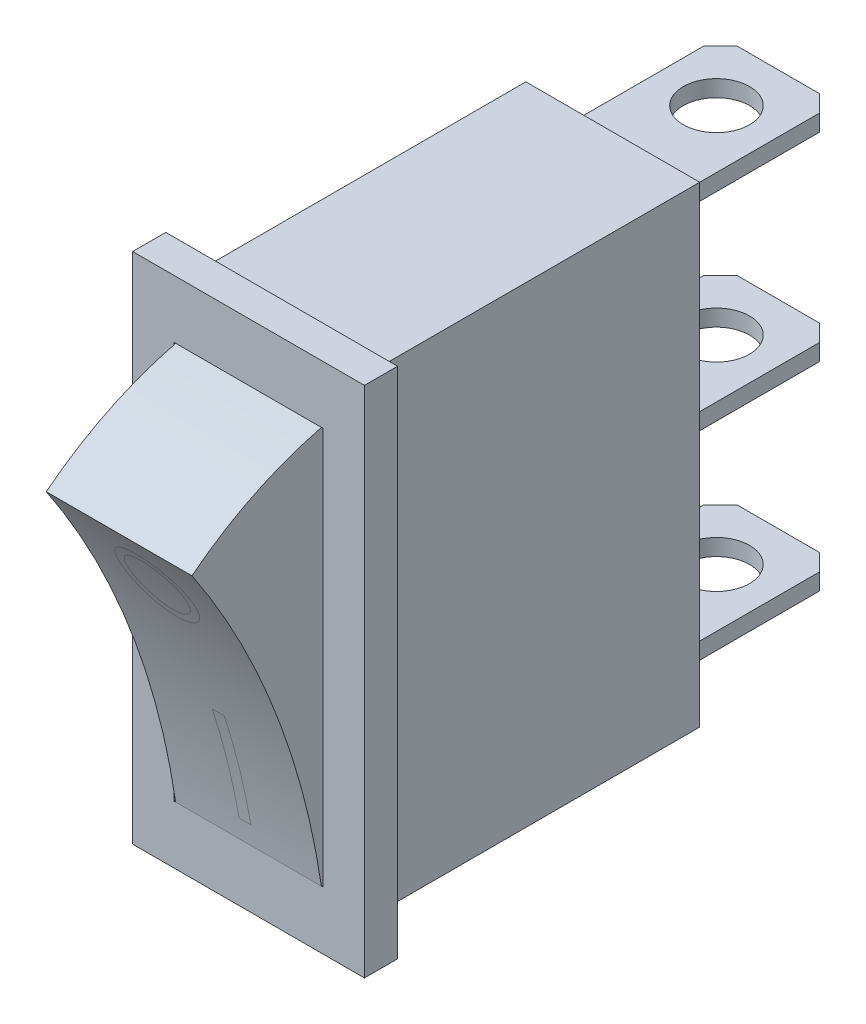
SolidWorks part; units mm, degrees
material "ABS"
ref_plane "Front Plane" through (0, 0, 0) normal (0, 0, 1) x (1, 0, 0)
ref_plane "Top Plane" through (0, 0, 0) normal (0, 1, 0) x (1, 0, 0)
ref_plane "Right Plane" through (0, 0, 0) normal (1, 0, 0) x (0, 0, -1)
sketch "Sketch1" plane through (0, 0, 0) normal (0, 0, 1) x (1, 0, 0)
  line L1 (-7, 15.5) -> (7, 15.5)
  line L2 (-7, 15.5) -> (-7, -15.5)
  line L3 (-7, -15.5) -> (7, -15.5)
  line L4 (7, 15.5) -> (7, -15.5)
  line L5 (-7, 15.5) -> (7, -15.5) construction
  line L6 (-7, -15.5) -> (7, 15.5) construction
  line L7 (-4.5, 12) -> (4.5, 12)
  line L8 (-4.5, 12) -> (-4.5, -12)
  line L9 (-4.5, -12) -> (4.5, -12)
  line L10 (4.5, 12) -> (4.5, -12)
  line L11 (-4.5, 12) -> (4.5, -12) construction
  line L12 (-4.5, -12) -> (4.5, 12) construction
  point P0 (0, 0)
  point P6 (0, 0)
  dimension "D1" = 31
  dimension "D2" = 14
  dimension "D3" = 24
  dimension "D4" = 9
extrude "Boss-Extrude1" add sketch "Sketch1" along normal blind 2
sketch "Sketch2" plane through (0, 0, 0) normal (0, 0, 1) x (1, 0, 0)
  line L0 (4.5, -12) -> (4.5, 12) construction
  line L1 (-5.25, 14.25) -> (5.25, 14.25)
  line L2 (-5.25, 14.25) -> (-5.25, -14.25)
  line L3 (-5.25, -14.25) -> (5.25, -14.25)
  line L4 (5.25, 14.25) -> (5.25, -14.25)
  line L5 (-5.25, 14.25) -> (5.25, -14.25) construction
  line L6 (-5.25, -14.25) -> (5.25, 14.25) construction
  line L7 (-4.5, -12) -> (4.5, -12) construction
  line L8 (-4.5, 12) -> (-4.5, -12) construction
  line L9 (4.5, 12) -> (-4.5, 12) construction
  line L10 (4.5, -12) -> (4.5, 12)
  line L11 (-4.5, -12) -> (4.5, -12)
  line L12 (-4.5, 12) -> (-4.5, -12)
  line L13 (4.5, 12) -> (-4.5, 12)
  point P0 (0, 0)
  dimension "D1" = 10.5
  dimension "D2" = 28.5
extrude "Boss-Extrude2" add sketch "Sketch2" against normal blind 20
sketch "Sketch3" plane through (0, 0, -20) normal (0, 0, -1) x (-1, 0, 0)
  line L4 (-5.25, 14.25) -> (-5.25, -14.25)
  line L5 (-5.25, -14.25) -> (5.25, -14.25)
  line L6 (5.25, -14.25) -> (5.25, 14.25)
  line L7 (5.25, 14.25) -> (-5.25, 14.25)
  line L8 (-5.25, 14.25) -> (-5.25, -14.25)
  line L9 (-5.25, -14.25) -> (5.25, -14.25)
  line L10 (5.25, -14.25) -> (5.25, 14.25)
  line L11 (5.25, 14.25) -> (-5.25, 14.25)
  dimension "D1" = 0
extrude "Boss-Extrude3" add sketch "Sketch3" against normal blind 2
sketch "Sketch4" plane through (0, 0, -20) normal (0, 0, -1) x (-1, 0, 0)
  line L1 (-3.5, 0.5) -> (3.5, 0.5)
  line L2 (-3.5, 0.5) -> (-3.5, -0.5)
  line L3 (-3.5, -0.5) -> (3.5, -0.5)
  line L4 (3.5, 0.5) -> (3.5, -0.5)
  line L5 (-3.5, 0.5) -> (3.5, -0.5) construction
  line L6 (-3.5, -0.5) -> (3.5, 0.5) construction
  point P0 (0, 0)
  dimension "D1" = 1
  dimension "D2" = 7
extrude "Boss-Extrude4" add sketch "Sketch4" along normal blind 10 separate body
chamfer "Chamfer1" distance 1 angle 45 2 edges at (3.5, 0, -30) (-3.5, 0, -30)
pattern_linear "LPattern1" count 2 spacing 12 along (0, -1, 0) count 2 spacing 12 along (0, 1, 0) of bodies 104
sketch "Sketch6" plane through (0, -12.5, 0) normal (0, -1, 0) x (1, 0, 0)
  circle A0 centre (0, -26.2612) radius 2
  dimension "D1" = 4
extrude "Cut-Extrude1" cut sketch "Sketch6" against normal through all
sketch "Sketch7" plane through (0, 0, 0) normal (1, 0, 0) x (0, 0, -1)
  line L0 (18, -12) -> (-2, -12)
  line L1 (18, -12) -> (-2, -12) construction
  line L2 (-2, 12) -> (18, 12)
  line L3 (-2, 12) -> (18, 12) construction
  line L4 (-2, -12) -> (3.0352, -12)
  line L5 (3.0352, -12) -> (3.0352, 12)
  line L6 (3.0352, 12) -> (-2, 12)
  arc A0 (-2, -12) -> (-9.8183, 8.1466) centre (-50.4905, -19.2273) ccw
  arc A1 (-9.8183, 8.1466) -> (-2, 12) centre (3.0352, -8.0743) cw
extrude "Boss-Extrude5" add sketch "Sketch7" along normal mid plane 8.8 separate body
sketch "Sketch8" plane through (0, 0, 0) normal (0, 0, 1) x (1, 0, 0)
  line L1 (-0.36, -4.1904) -> (0.36, -4.1904)
  line L2 (-0.36, -4.1904) -> (-0.36, -10.7077)
  line L3 (-0.36, -10.7077) -> (0.36, -10.7077)
  line L4 (0.36, -4.1904) -> (0.36, -10.7077)
  line L5 (-0.36, -4.1904) -> (0.36, -10.7077) construction
  line L6 (-0.36, -10.7077) -> (0.36, -4.1904) construction
  circle A0 centre (0, 4.3364) radius 2.2538
  circle A1 centre (0, 4.3364) radius 1.7538
  point P0 (0, -7.4491)
  dimension "D1" = 0.5
split line "Split Line1"
